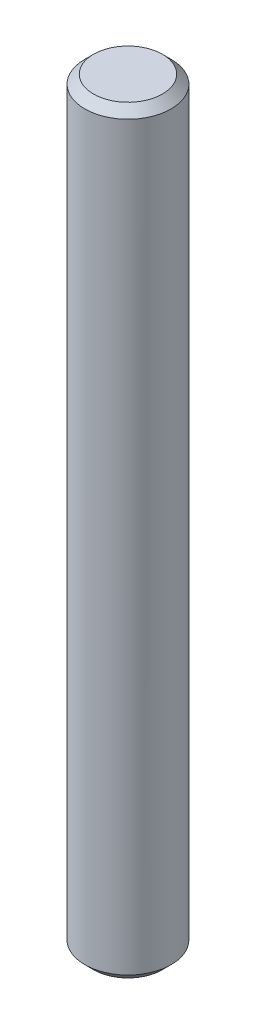
SolidWorks part; units mm, degrees
ref_plane "前视基准面" through (0, 0, 0) normal (0, 0, 1) x (1, 0, 0)
ref_plane "上视基准面" through (0, 0, 0) normal (0, 1, 0) x (1, 0, 0)
ref_plane "右视基准面" through (0, 0, 0) normal (1, 0, 0) x (0, 0, -1)
other "Configuration Table"
sketch "草图1" plane through (0, 0, 0) normal (0, 0, 1) x (1, 0, 0)
  line L0 (0, 61.8249) -> (0, -44.5084) construction
  line L1 (0, 44) -> (5, 44)
  line L2 (5, 44) -> (5, 29)
  line L6 (5, -29) -> (5, -44)
  line L7 (5, -44) -> (0, -44)
  line L8 (0, 0) -> (41.6667, 0) construction
  line L9 (0, 44) -> (0, -44)
  line L10 (5, 29) -> (5, -29)
  dimension "D1" = 5
  dimension "D2" = 5
  dimension "D5" = 88
revolve "旋转1" add sketch "草图1" angle 360 about L9
chamfer "倒角1" distance 1 angle 45 2 edges at (-5, -44, 0) (-5, 44, 0)
